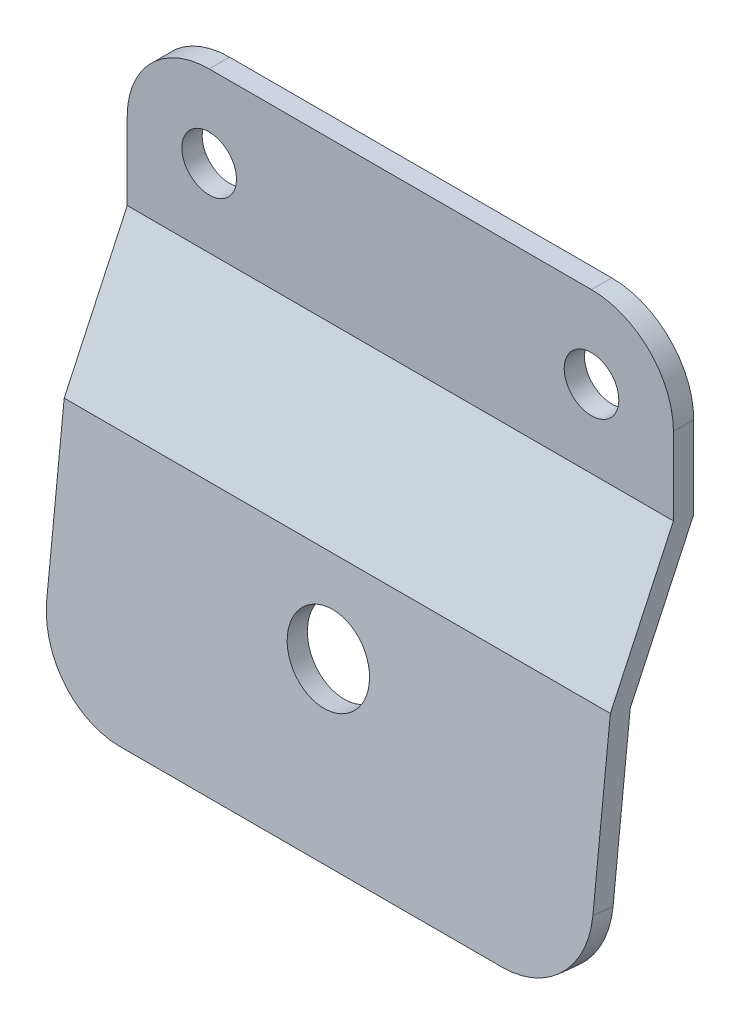
SolidWorks part; units mm, degrees
ref_plane "front" through (0, 0, 0) normal (0, 0, 1) x (1, 0, 0)
ref_plane "top" through (0, 0, 0) normal (0, 1, 0) x (1, 0, 0)
ref_plane "right" through (0, 0, 0) normal (1, 0, 0) x (0, 0, -1)
sketch "Sketch1" plane through (0, 0, 0) normal (1, 0, 0) x (0, 0, -1)
  line L0 (0, 19.05) -> (0, 0)
  line L1 (0, 0) -> (-7.3853, -15.8379)
  line L2 (-7.3853, -15.8379) -> (-10.3722, -44.2564)
  dimension "D1" = 19.05
  dimension "D2" = 17.4752
  dimension "D3" = 25
  dimension "D4" = 28.575
  dimension "D5" = 19
  dimension "D6" = 63.3064
  dimension "D7" = 6
  dimension "D8" = 7.3853
extrude "Extrude-Thin1" add sketch "Sketch1" along normal mid plane 63.5 thin
sketch "Sketch2" plane through (0, -51.1695, 13.4741) normal (0, 0.1045, 0.9945) x (-1, 0, 0)
  line L1 (-31.75, -7.1995) -> (31.75, -7.1995) construction
  circle A0 centre (0, -26.2495) radius 4.7625
  dimension "D2" = 9.525
  dimension "D1" = 19.05
extrude "Cut-Extrude1" cut sketch "Sketch2" against normal through all and the other way through all
sketch "Sketch3" plane through (0, 0, 0) normal (0, 0, -1) x (-1, 0, 0)
  line L0 (0, 0) -> (0, 17.78) construction
  line L1 (-31.75, 19.05) -> (31.75, 19.05) construction
  circle A0 centre (-22.225, 9.525) radius 3.175
  circle A1 centre (22.225, 9.525) radius 3.175
  dimension "D3" = 6.35
  dimension "D1" = 44.45
  dimension "D2" = 9.525
extrude "Cut-Extrude2" cut sketch "Sketch3" against normal through all
sketch "Sketch4" plane through (0, 0, 0) normal (0, 0, 1) x (1, 0, 0)
  circle A0 centre (-22.225, 9.525) radius 3.175 construction
  circle A1 centre (22.225, 9.525) radius 3.175 construction
  point P0 (22.225, 9.525)
  point P1 (-22.225, 9.525)
fillet "Fillet1" radius 9.525 4 edges at (-31.75, -44.1329, 11.5469) (31.75, -44.1329, 11.5469) (31.75, 19.05, 1.1811) (-31.75, 19.05, 1.1811)
sketch "Sketch5" plane through (0, 0.5947, 5.6582) normal (0, -0.1045, -0.9945) x (-1, 0, 0)
  line L1 (0, -34.3044) -> (7.1501, -30.1762)
  line L2 (7.1501, -30.1762) -> (7.1501, -21.92)
  line L3 (7.1501, -21.92) -> (0, -17.7919)
  line L4 (0, -17.7919) -> (-7.1501, -21.92)
  line L5 (-7.1501, -21.92) -> (-7.1501, -30.1762)
  line L6 (-7.1501, -30.1762) -> (0, -34.3044)
  circle A0 centre (0, -26.0481) radius 7.1501 construction
  circle A1 centre (0, -26.0481) radius 4.7625 construction
  dimension "D1" = 14.3002
extrude "Extrude1" [suppressed] add sketch "Sketch5" along normal blind 6.35
sketch "Sketch6" plane through (0, 0.8416, 8.0075) normal (0, 0.1045, 0.9945) x (1, 0, 0)
  circle A0 centre (0, -26.0481) radius 4.7625 construction
  point P0 (0, -26.0481)
